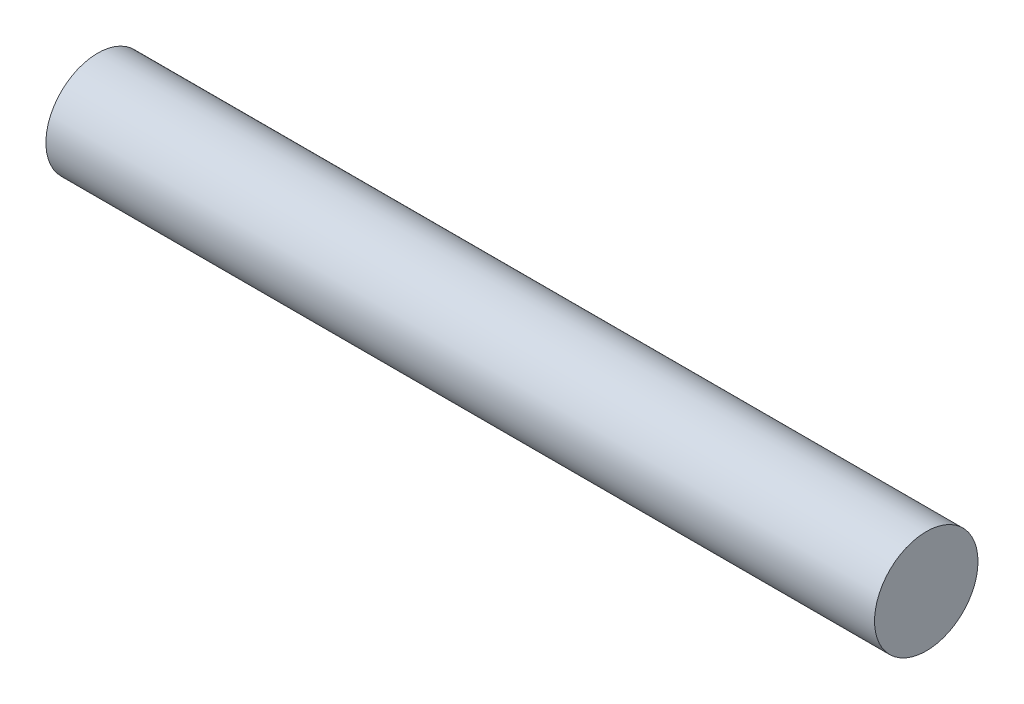
SolidWorks part; units mm, degrees
ref_plane "Front Plane" through (0, 0, 0) normal (0, 0, 1) x (1, 0, 0)
ref_plane "Top Plane" through (0, 0, 0) normal (0, 1, 0) x (1, 0, 0)
ref_plane "Right Plane" through (0, 0, 0) normal (1, 0, 0) x (0, 0, -1)
sketch "Sketch1" plane through (0, 0, 0) normal (1, 0, 0) x (0, 0, -1)
  circle A0 centre (0, 0) radius 1
  dimension "D1" = 2
extrude "Boss-Extrude1" add sketch "Sketch1" along normal mid plane 16.0172
